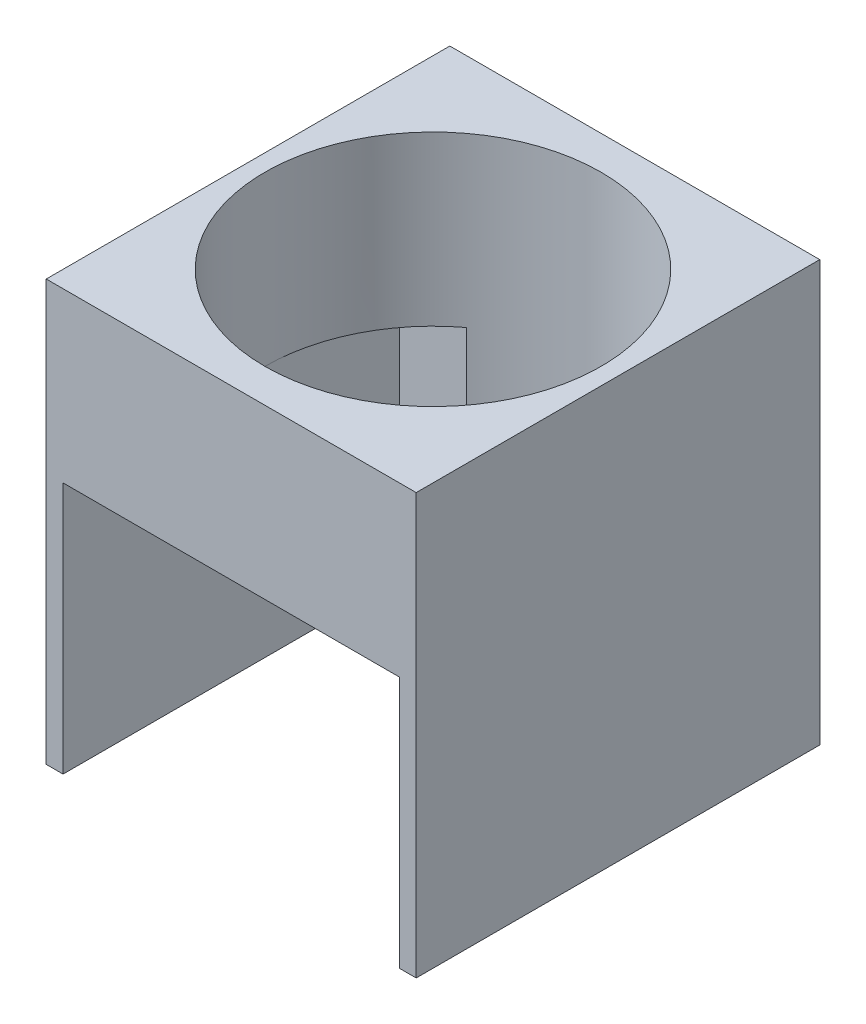
SolidWorks part; units mm, degrees
ref_plane "정면" through (0, 0, 0) normal (0, 0, 1) x (1, 0, 0)
ref_plane "윗면" through (0, 0, 0) normal (0, 1, 0) x (1, 0, 0)
ref_plane "우측면" through (0, 0, 0) normal (1, 0, 0) x (0, 0, -1)
sketch "Sketch1" plane through (0, 0, 0) normal (0, 1, 0) x (1, 0, 0)
  line L1 (0, 0) -> (670, 0)
  line L2 (0, 0) -> (0, 120)
  line L3 (0, 120) -> (670, 120)
  line L4 (670, 0) -> (670, 120)
  dimension "700" = 670
  dimension "D2" = 120
extrude "Boss-Extrude1" add sketch "Sketch1" along normal blind 530
sketch "Sketch2" plane through (0, 0, 0) normal (0, 0, 1) x (1, 0, 0)
  line L0 (0, 530) -> (0, 0) construction
  line L1 (10, 280) -> (110, 280)
  line L2 (10, 280) -> (10, 480)
  line L3 (10, 480) -> (110, 480)
  line L4 (110, 280) -> (110, 480)
  line L5 (0, 0) -> (670, 0) construction
  line L6 (120, 280) -> (120, 480)
  line L7 (120, 280) -> (220, 280)
  line L8 (220, 280) -> (220, 480)
  line L9 (120, 480) -> (220, 480)
  line L10 (230, 280) -> (230, 480)
  line L11 (230, 280) -> (330, 280)
  line L12 (330, 280) -> (330, 480)
  line L13 (230, 480) -> (330, 480)
  line L14 (340, 280) -> (340, 480)
  line L15 (340, 280) -> (440, 280)
  line L16 (440, 280) -> (440, 480)
  line L17 (340, 480) -> (440, 480)
  line L18 (450, 280) -> (450, 480)
  line L19 (450, 280) -> (550, 280)
  line L20 (550, 280) -> (550, 480)
  line L21 (450, 480) -> (550, 480)
  line L22 (560, 280) -> (560, 480)
  line L23 (560, 280) -> (660, 280)
  line L24 (660, 280) -> (660, 480)
  line L25 (560, 480) -> (660, 480)
  line L27 (10, 10) -> (660, 10)
  line L28 (10, 10) -> (10, 260)
  line L29 (10, 260) -> (660, 260)
  line L30 (660, 10) -> (660, 260)
  line L31 (0, 530) -> (670, 530) construction
  point P6 (10, 380)
  dimension "D1" = 100
  dimension "D2" = 200
  dimension "D3" = 10
  dimension "D4" = 50
  dimension "D6" = 10
  dimension "D7" = 20
  dimension "D5" = 6
extrude "Cut-Extrude1" cut sketch "Sketch2" against normal blind 100
sketch "Sketch3" plane through (0, 530, 0) normal (0, 1, 0) x (1, 0, 0)
  line L1 (670, 120) -> (0, 120) construction
  line L2 (0, 120) -> (0, 0) construction
  circle A0 centre (60, 60) radius 50
  circle A1 centre (170, 60) radius 50
  circle A2 centre (280, 60) radius 50
  circle A3 centre (390, 60) radius 50
  circle A4 centre (500, 60) radius 50
  circle A5 centre (610, 60) radius 50
  dimension "D1" = 100
  dimension "D2" = 10
  dimension "D3" = 10
  dimension "D4" = 6
extrude "Cut-Extrude2" cut sketch "Sketch3" against normal blind 260
hole_wizard "Ø12.0 (12) Diameter Hole2" positions "3DSketch1" profile "Sketch7" hole size "Ø12.0" standard "Ansi Metric"
sketch3d "3DSketch1"
  point P0 (59.7046, 270, -102.4117)
  point P2 (171.5567, 270, -102.6076)
  point P4 (280.8723, 270, -102.3969)
  point P6 (391.0687, 270, -102.7535)
  point P8 (500.7133, 270, -101.754)
  point P10 (609.5165, 270, -101.1227)
sketch "Sketch7" plane through (59.7046, 270, -102.4117) normal (1, 0, 0) x (0, 0, 1)
  line L0 (0, 0) -> (0, 33.6052)
  line L1 (0, 33.6052) -> (6, 30)
  line L2 (6, 30) -> (6, 0)
  line L5 (6, 0) -> (0, 0)
  line L10 (0, 33.6052) -> (-6, 30) construction
  line L11 (0, -6.35) -> (0, 107.95) construction
  dimension "구멍 지름" = 12
  dimension "구멍 깊이" = 30
  dimension "드릴 각도" = 118
sketch "Sketch8" plane through (0, 0, 0) normal (0, 0, 1) x (1, 0, 0)
  line L0 (660, 280) -> (660, 480) construction
  line L1 (10, 280) -> (660, 280)
  line L2 (10, 280) -> (10, 330)
  line L3 (10, 330) -> (660, 330)
  line L4 (660, 280) -> (660, 330)
  dimension "D1" = 50
extrude "Boss-Extrude2" add sketch "Sketch8" against normal blind 5
sketch "Sketch9" plane through (670, 0, 0) normal (1, 0, 0) x (0, 0, -1)
  line L0 (0, 530) -> (0, 0) construction
  line L1 (10, 10) -> (20, 10)
  line L2 (10, 10) -> (10, 260)
  line L3 (10, 260) -> (20, 260)
  line L4 (20, 10) -> (20, 260)
  line L5 (0, 0) -> (120, 0) construction
  dimension "D1" = 10
  dimension "D2" = 10
  dimension "D3" = 10
  dimension "D4" = 250
extrude "Cut-Extrude3" cut sketch "Sketch9" against normal blind 717
sketch "Sketch10" plane through (0, 10, 0) normal (0, 1, 0) x (1, 0, 0)
  line L0 (670, 120) -> (0, 120) construction
  line L1 (365, 61.9436) -> (350, 87.9243)
  line L2 (350, 87.9243) -> (320, 87.9243)
  line L3 (320, 87.9243) -> (305, 61.9436)
  line L4 (305, 61.9436) -> (320, 35.9628)
  line L5 (320, 35.9628) -> (350, 35.9628)
  line L6 (350, 35.9628) -> (365, 61.9436)
  line L7 (0, 120) -> (0, 0) construction
  circle A0 centre (335, 61.9436) radius 25.9808 construction
  dimension "D1" = 60
  dimension "D2" = 305
extrude "Cut-Extrude4" cut sketch "Sketch10" against normal blind 5
sketch "Sketch11" plane through (0, 0, -100) normal (0, 0, 1) x (1, 0, 0)
  line L0 (10, 10) -> (660, 10) construction
  line L1 (250, 10) -> (260, 10)
  line L2 (250, 10) -> (250, 110)
  line L3 (250, 110) -> (260, 110)
  line L4 (260, 10) -> (260, 110)
  line L5 (660, 10) -> (660, 260) construction
  line L6 (410, 10) -> (420, 10)
  line L7 (410, 10) -> (410, 110)
  line L8 (410, 110) -> (420, 110)
  line L9 (420, 10) -> (420, 110)
  line L10 (25, 198.4569) -> (325, 145.5588)
  line L11 (325, 145.5588) -> (325, 122.0178)
  line L12 (325, 122.0178) -> (345, 122.0178)
  line L13 (345, 122.0178) -> (345, 145.5588)
  line L14 (345, 145.5588) -> (645, 198.4569)
  line L15 (645, 198.4569) -> (25, 198.4569)
  point P18 (345, 133.7883)
  dimension "D1" = 10
  dimension "D2" = 10
  dimension "D3" = 100
  dimension "D4" = 100
  dimension "D5" = 150
  dimension "D6" = 240
  dimension "D7" = 20
  dimension "D8" = 65
  dimension "D9" = 100
  dimension "D10" = 620
  dimension "D11" = 100
extrude "Boss-Extrude3" add sketch "Sketch11" along normal blind 78 separate body
sketch "Sketch12" plane through (0, 0, -100) normal (0, 0, 1) x (1, 0, 0)
  line L0 (660, 260) -> (10, 260) construction
  line L1 (75.1986, 260) -> (95.1986, 260)
  line L2 (75.1986, 260) -> (75.1986, 230)
  line L3 (75.1986, 230) -> (95.1986, 230)
  line L4 (95.1986, 260) -> (95.1986, 230)
  line L5 (65.1986, 260) -> (65.1986, 240) construction
  line L6 (185.1986, 260) -> (185.1986, 230)
  line L7 (185.1986, 260) -> (205.1986, 260)
  line L8 (205.1986, 260) -> (205.1986, 230)
  line L9 (185.1986, 230) -> (205.1986, 230)
  line L10 (295.1986, 260) -> (295.1986, 230)
  line L11 (295.1986, 260) -> (315.1986, 260)
  line L12 (315.1986, 260) -> (315.1986, 230)
  line L13 (295.1986, 230) -> (315.1986, 230)
  line L14 (405.1986, 260) -> (405.1986, 230)
  line L15 (405.1986, 260) -> (425.1986, 260)
  line L16 (425.1986, 260) -> (425.1986, 230)
  line L17 (405.1986, 230) -> (425.1986, 230)
  line L18 (515.1986, 260) -> (515.1986, 230)
  line L19 (515.1986, 260) -> (535.1986, 260)
  line L20 (535.1986, 260) -> (535.1986, 230)
  line L21 (515.1986, 230) -> (535.1986, 230)
  line L22 (625.1986, 260) -> (625.1986, 230)
  line L23 (625.1986, 260) -> (645.1986, 260)
  line L24 (645.1986, 260) -> (645.1986, 230)
  line L25 (625.1986, 230) -> (645.1986, 230)
  dimension "D1" = 20
  dimension "D2" = 30
  dimension "D3" = 10
  dimension "D4" = 6
extrude "Cut-Extrude5" cut sketch "Sketch12" against normal blind 80
sketch "Sketch15" plane through (345, 0, 0) normal (1, 0, 0) x (0, 0, -1)
  line L0 (20, 10) -> (20, 260) construction
  line L1 (20, 121.4638) -> (50, 121.4638)
  line L2 (20, 121.4638) -> (20, 145)
  line L3 (20, 145) -> (50, 145)
  line L4 (50, 121.4638) -> (50, 145)
  line L5 (120, 530) -> (120, 0) construction
  line L6 (100, 116.0134) -> (70, 116.0134)
  line L7 (100, 116.0134) -> (100, 145)
  line L8 (100, 145) -> (70, 145)
  line L9 (70, 116.0134) -> (70, 145)
  line L10 (20, 260) -> (10, 260) construction
  dimension "D1" = 20
  dimension "D2" = 20
  dimension "D3" = 115
  dimension "D4" = 30
extrude "Cut-Extrude7" cut sketch "Sketch15" against normal blind 35
shell "Shell1" thickness 3
sketch "Sketch16" plane through (0, 122.0178, 0) normal (0, -1, 0) x (1, 0, 0)
  line L0 (345, -50) -> (325, -50) construction
  line L1 (328, -53) -> (342, -53)
  line L2 (328, -53) -> (328, -67)
  line L3 (328, -67) -> (342, -67)
  line L4 (342, -53) -> (342, -67)
  line L5 (325, -50) -> (325, -70) construction
  line L6 (345, -50) -> (345, -70) construction
  line L7 (325, -70) -> (345, -70) construction
  dimension "D1" = 3
  dimension "D2" = 3
  dimension "D3" = 3
  dimension "D4" = 3
extrude "Cut-Extrude8" cut sketch "Sketch16" against normal blind 35
sketch "Sketch17" plane through (0, 0, 0) normal (0, 0, 1) x (1, 0, 0)
  text T0 "<b>DIFF_USER</b>" font "Britannic Bold" height in points 72
extrude "Boss-Extrude4" add sketch "Sketch17" along normal blind 5
sketch "Sketch18" plane through (0, 0, 0) normal (0, 0, 1) x (1, 0, 0)
  line L0 (670, 530) -> (670, 0) construction
  line L1 (0, 0) -> (670, 0)
  line L2 (0, 0) -> (0, 280)
  line L3 (0, 280) -> (670, 280)
  line L4 (670, 0) -> (670, 280)
  dimension "D1" = 280
extrude "Cut-Extrude10" cut sketch "Sketch18" against normal blind 159
sketch "Sketch19" plane through (0, 0, 0) normal (0, 0, 1) x (1, 0, 0)
  line L0 (0, 530) -> (670, 530) construction
  line L1 (0, 280) -> (115, 280)
  line L2 (0, 280) -> (0, 530)
  line L3 (0, 530) -> (115, 530)
  line L4 (115, 280) -> (115, 530)
  line L6 (670, 280) -> (225, 280)
  line L7 (670, 280) -> (670, 530)
  line L8 (670, 530) -> (225, 530)
  line L9 (225, 280) -> (225, 530)
  dimension "D1" = 115
  dimension "D2" = 445
extrude "Cut-Extrude11" cut sketch "Sketch19" against normal through all both and the other way through all
sketch "Sketch20" plane through (0, 0, 0) normal (0, 0, 1) x (1, 0, 0)
  line L0 (225, 280) -> (225, 530) construction
  line L1 (115, 280) -> (225, 280)
  line L2 (115, 280) -> (115, 405)
  line L3 (115, 405) -> (225, 405)
  line L4 (225, 280) -> (225, 405)
extrude "Cut-Extrude12" cut sketch "Sketch20" against normal through all both and the other way through all
